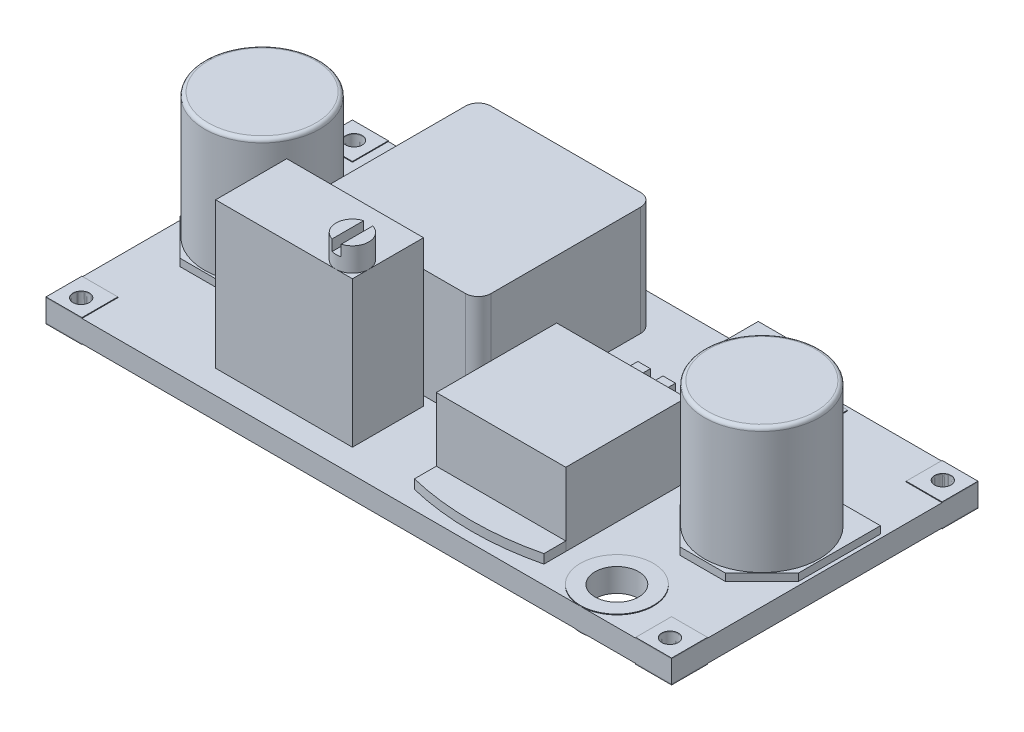
SolidWorks part; units mm, degrees
ref_plane "Front Plane" through (0, 0, 0) normal (0, 0, 1) x (1, 0, 0)
ref_plane "Top Plane" through (0, 0, 0) normal (0, 1, 0) x (1, 0, 0)
ref_plane "Right Plane" through (0, 0, 0) normal (1, 0, 0) x (0, 0, -1)
sketch "Sketch1" plane through (0, 0, 0) normal (0, 1, 0) x (1, 0, 0)
  line L1 (-21.7805, 10.668) -> (21.7805, 10.668)
  line L2 (-21.7805, 10.668) -> (-21.7805, -10.668)
  line L3 (-21.7805, -10.668) -> (21.7805, -10.668)
  line L4 (21.7805, 10.668) -> (21.7805, -10.668)
  line L5 (-21.7805, 10.668) -> (21.7805, -10.668) construction
  line L6 (-21.7805, -10.668) -> (21.7805, 10.668) construction
  circle A0 centre (-15.4305, 8.128) radius 1.651
  circle A1 centre (15.4305, -8.128) radius 1.651
  point P0 (0, 0)
  dimension "D3" = 3.302
  dimension "D1" = 43.561
  dimension "D2" = 21.336
  dimension "D4" = 6.35
  dimension "D5" = 6.35
  dimension "D6" = 2.54
  dimension "D7" = 2.54
extrude "Boss-Extrude1" add sketch "Sketch1" along normal blind 1.524
sketch "Sketch2" plane through (0, 1.524, 0) normal (0, 1, 0) x (1, 0, 0)
  line L0 (21.7805, 10.668) -> (-21.7805, 10.668) construction
  line L1 (-21.7805, -10.668) -> (21.7805, -10.668) construction
  line L3 (-21.7805, 10.668) -> (-19.2805, 10.668)
  line L4 (-21.7805, 10.668) -> (-21.7805, 8.168)
  line L5 (-21.7805, 8.168) -> (-19.2805, 8.168)
  line L6 (-19.2805, 10.668) -> (-19.2805, 8.168)
  line L7 (21.7805, 10.668) -> (19.2805, 10.668)
  line L8 (21.7805, 10.668) -> (21.7805, 8.168)
  line L9 (21.7805, 8.168) -> (19.2805, 8.168)
  line L10 (19.2805, 10.668) -> (19.2805, 8.168)
  line L11 (21.7805, -10.668) -> (19.2805, -10.668)
  line L12 (21.7805, -10.668) -> (21.7805, -8.168)
  line L13 (21.7805, -8.168) -> (19.2805, -8.168)
  line L14 (19.2805, -10.668) -> (19.2805, -8.168)
  line L15 (-21.7805, -10.668) -> (-19.2805, -10.668)
  line L16 (-21.7805, -10.668) -> (-21.7805, -8.168)
  line L17 (-21.7805, -8.168) -> (-19.2805, -8.168)
  line L18 (-19.2805, -10.668) -> (-19.2805, -8.168)
  circle A4 centre (-15.4305, 8.128) radius 1.651 construction
  circle A5 centre (15.4305, -8.128) radius 2.54
  circle A6 centre (-15.4305, 8.128) radius 2.54
  circle A9 centre (-15.4305, 8.128) radius 1.524
  circle A10 centre (-15.4305, 8.128) radius 1.524
  circle A12 centre (15.4305, -8.128) radius 1.524
  circle A13 centre (15.4305, -8.128) radius 1.524
  dimension "D3" = 2.5
  dimension "D1" = 0.127
  dimension "D2" = 0.127
extrude "Boss-Extrude2" add sketch "Sketch2" against normal offset from surface 0.0508 and the other way blind 0.0508 separate body up to face at (0, 0, 0) offset beyond the face yes
sketch "Sketch3" plane through (0, 1.524, 0) normal (0, 1, 0) x (1, 0, 0)
  line L0 (-21.5265, 4.1275) -> (-13.2715, -4.1275) construction
  line L1 (-21.5265, 4.1275) -> (-13.2715, 4.1275)
  line L2 (-21.5265, 4.1275) -> (-21.5265, -1.5875)
  line L3 (-18.9865, -4.1275) -> (-15.8115, -4.1275)
  line L4 (-13.2715, 4.1275) -> (-13.2715, -1.5875)
  line L5 (13.2715, 4.1275) -> (21.5265, 4.1275)
  line L6 (13.2715, 4.1275) -> (13.2715, -1.5875)
  line L7 (15.8115, -4.1275) -> (18.9865, -4.1275)
  line L8 (21.5265, 4.1275) -> (21.5265, -1.5875)
  line L9 (-21.7805, 10.668) -> (-21.7805, -10.668) construction
  line L10 (-21.5265, -1.5875) -> (-18.9865, -4.1275)
  line L11 (-15.8115, -4.1275) -> (-13.2715, -1.5875)
  line L12 (13.2715, -1.5875) -> (15.8115, -4.1275)
  line L13 (18.9865, -4.1275) -> (21.5265, -1.5875)
  line L14 (13.2715, -4.1275) -> (21.5265, 4.1275) construction
  line L15 (-17.399, 4.1275) -> (-17.399, -4.1275) construction
  line L16 (17.399, 4.1275) -> (17.399, -4.1275) construction
  line L17 (-17.399, 0) -> (17.399, 0) construction
  point P1 (-13.2715, -4.1275)
  point P2 (-21.5265, -4.1275)
  point P5 (21.5265, -4.1275)
  point P6 (13.2715, -4.1275)
  dimension "D1" = 8.255
  dimension "D2" = 0.254
extrude "Boss-Extrude3" add sketch "Sketch3" along normal blind 0.508 separate body
sketch "Sketch4" plane through (0, 2.032, 0) normal (0, 1, 0) x (1, 0, 0)
  circle A0 centre (-17.399, 0) radius 4.0005
  circle A1 centre (17.399, 0) radius 4.0005
  dimension "D1" = 8.001
extrude "Boss-Extrude4" add sketch "Sketch4" along normal blind 8.763 separate body
fillet "Fillet1" radius 0.254 1 edges at (-17.399, 10.795, 4.0005)
fillet "Fillet2" radius 0.254 1 edges at (17.399, 10.795, 4.0005)
sketch "Sketch5" plane through (0, 1.524, 0) normal (0, 1, 0) x (1, 0, 0)
  line L0 (21.7805, 10.668) -> (-21.7805, 10.668) construction
  line L1 (-10.2235, 8.763) -> (0.1905, 8.763)
  line L2 (-11.1125, 7.874) -> (-11.1125, -2.54)
  line L3 (-10.2235, -3.429) -> (0.1905, -3.429)
  line L4 (1.0795, 7.874) -> (1.0795, -2.54)
  line L5 (-11.1125, 8.763) -> (1.0795, -3.429) construction
  line L6 (-11.1125, -3.429) -> (1.0795, 8.763) construction
  line L7 (-21.7805, 10.668) -> (-21.7805, -10.668) construction
  arc A0 (-11.1125, -2.54) -> (-10.2235, -3.429) centre (-10.2235, -2.54) ccw
  arc A1 (0.1905, -3.429) -> (1.0795, -2.54) centre (0.1905, -2.54) ccw
  arc A2 (0.1905, 8.763) -> (1.0795, 7.874) centre (0.1905, 7.874) cw
  arc A3 (-10.2235, 8.763) -> (-11.1125, 7.874) centre (-10.2235, 7.874) ccw
  point P0 (-5.0165, 2.667)
  dimension "D4" = 0.889
  dimension "D1" = 12.192
  dimension "D2" = 1.905
  dimension "D3" = 10.668
extrude "Boss-Extrude5" add sketch "Sketch5" along normal blind 7.62 separate body
sketch "Sketch6" plane through (0, 1.524, 0) normal (0, 1, 0) x (1, 0, 0)
  line L0 (-21.7805, -10.668) -> (21.7805, -10.668) construction
  line L1 (-11.6205, -4.064) -> (-2.0955, -4.064)
  line L2 (-11.6205, -4.064) -> (-11.6205, -9.017)
  line L3 (-11.6205, -9.017) -> (-2.0955, -9.017)
  line L4 (-2.0955, -4.064) -> (-2.0955, -9.017)
  line L5 (-11.6205, -4.064) -> (-2.0955, -9.017) construction
  line L6 (-11.6205, -9.017) -> (-2.0955, -4.064) construction
  line L7 (-21.7805, 10.668) -> (-21.7805, -10.668) construction
  point P0 (-6.858, -6.5405)
  dimension "D1" = 9.525
  dimension "D2" = 4.953
  dimension "D3" = 1.651
  dimension "D4" = 10.16
extrude "Boss-Extrude6" add sketch "Sketch6" along normal blind 10.16 separate body
sketch "Sketch7" plane through (0, 11.684, 0) normal (0, 1, 0) x (1, 0, 0)
  line L0 (-11.6205, -9.017) -> (-2.0955, -9.017) construction
  line L1 (-2.0955, -9.017) -> (-2.0955, -4.064) construction
  circle A0 centre (-3.2385, -7.874) radius 1.143
  dimension "D1" = 2.286
extrude "Boss-Extrude7" add sketch "Sketch7" along normal blind 1.651
sketch "Sketch8" plane through (0, 13.335, 0) normal (0, 1, 0) x (1, 0, 0)
  line L1 (-2.921, -6.731) -> (-3.556, -6.731)
  line L2 (-2.921, -6.731) -> (-2.921, -9.017)
  line L3 (-2.921, -9.017) -> (-3.556, -9.017)
  line L4 (-3.556, -6.731) -> (-3.556, -9.017)
  line L5 (-2.921, -6.731) -> (-3.556, -9.017) construction
  line L6 (-2.921, -9.017) -> (-3.556, -6.731) construction
  circle A0 centre (-3.2385, -7.874) radius 1.143 construction
  point P0 (-3.2385, -7.874)
  dimension "D1" = 0.635
extrude "Cut-Extrude1" cut sketch "Sketch8" against normal blind 0.762
sketch "Sketch9" plane through (0, 1.524, 0) normal (0, 1, 0) x (1, 0, 0)
  line L0 (-21.7805, -10.668) -> (21.7805, -10.668) construction
  line L1 (11.6205, 0.508) -> (2.6035, 0.508)
  line L2 (11.6205, 0.508) -> (11.6205, -7.874)
  line L3 (11.6205, -7.874) -> (2.6035, -7.874)
  line L4 (2.6035, 0.508) -> (2.6035, -7.874)
  line L5 (11.6205, 0.508) -> (2.6035, -7.874) construction
  line L6 (11.6205, -7.874) -> (2.6035, 0.508) construction
  line L7 (21.7805, -10.668) -> (21.7805, 10.668) construction
  point P0 (7.112, -3.683)
  dimension "D1" = 9.017
  dimension "D2" = 8.382
  dimension "D3" = 2.794
  dimension "D4" = 10.16
extrude "Boss-Extrude8" add sketch "Sketch9" along normal blind 5.08 separate body
sketch "Sketch10" plane through (0, 1.524, 0) normal (0, 1, 0) x (1, 0, 0)
  line L0 (11.6205, -7.874) -> (11.6205, 0.508) construction
  line L1 (2.6035, -7.874) -> (11.6205, -7.874)
  line L2 (2.6035, -7.874) -> (2.6035, -9.398)
  line L4 (11.6205, -7.874) -> (11.6205, -9.398)
  arc A0 (2.6035, -9.398) -> (11.6205, -9.398) centre (7.112, 9.1108) ccw
  dimension "D2" = 19.05
  dimension "D1" = 1.524
extrude "Boss-Extrude9" add sketch "Sketch10" along normal blind 0.635 separate body
ref_plane "Plane1" through (7.112, 0, 0) normal (1, 0, 0) x (0, 0, -1)
sketch "Sketch11" plane through (7.112, 0, 0) normal (1, 0, 0) x (0, 0, -1)
  line L0 (0.508, 4.699) -> (1.4341, 4.699)
  line L1 (1.9057, 4.3797) -> (2.9203, 1.8433)
  line L2 (3.3919, 1.524) -> (5.588, 1.524)
  line L5 (-7.874, 1.524) -> (0.508, 1.524) construction
  line L6 (0.508, 6.604) -> (0.508, 1.524) construction
  line L7 (0.508, 6.604) -> (-7.874, 6.604) construction
  arc A0 (2.9203, 1.8433) -> (3.3919, 1.524) centre (3.3919, 2.032) ccw
  arc A1 (1.4341, 4.699) -> (1.9057, 4.3797) centre (1.4341, 4.191) cw
  point P15 (3.048, 1.524)
  point P18 (1.778, 4.699)
  dimension "D5" = 0.508
  dimension "D1" = 1.27
  dimension "D2" = 1.905
  dimension "D3" = 2.54
  dimension "D4" = 2.54
extrude "Extrude-Thin1" add sketch "Sketch11" along normal mid plane 7.874 separate body thin
sketch "Sketch12" plane through (0, 5.207, 0) normal (0, 1, 0) x (1, 0, 0)
  line L0 (11.049, 5.588) -> (3.175, 5.588) construction
  line L1 (4.0499, 5.588) -> (4.9248, 5.588)
  line L2 (4.0499, 5.588) -> (4.0499, 0.508)
  line L3 (4.0499, 0.508) -> (4.9248, 0.508)
  line L4 (4.9248, 5.588) -> (4.9248, 0.508)
  line L5 (11.049, 0.508) -> (3.175, 0.508) construction
  line L6 (5.7997, 5.588) -> (5.7997, 0.508)
  line L7 (5.7997, 5.588) -> (6.6746, 5.588)
  line L8 (6.6746, 5.588) -> (6.6746, 0.508)
  line L9 (5.7997, 0.508) -> (6.6746, 0.508)
  line L10 (7.5494, 5.588) -> (7.5494, 0.508)
  line L11 (7.5494, 5.588) -> (8.4243, 5.588)
  line L12 (8.4243, 5.588) -> (8.4243, 0.508)
  line L13 (7.5494, 0.508) -> (8.4243, 0.508)
  line L14 (9.2992, 5.588) -> (9.2992, 0.508)
  line L15 (9.2992, 5.588) -> (10.1741, 5.588)
  line L16 (10.1741, 5.588) -> (10.1741, 0.508)
  line L17 (9.2992, 0.508) -> (10.1741, 0.508)
  line L18 (3.175, 3.3919) -> (4.0499, 3.3919) construction
  line L19 (11.049, 3.3919) -> (3.175, 3.3919) construction
  line L20 (4.9248, 3.3919) -> (5.7997, 3.3919) construction
  line L21 (6.6746, 3.3919) -> (7.5494, 3.3919) construction
  line L22 (8.4243, 3.3919) -> (9.2992, 3.3919) construction
  line L23 (10.1741, 3.3919) -> (11.049, 3.3919) construction
  dimension "D1" = 4
extrude "Cut-Extrude2" cut sketch "Sketch12" against normal up to next
sketch "Sketch13" plane through (0, 1.524, 0) normal (0, 1, 0) x (1, 0, 0)
  line L0 (21.7805, 10.668) -> (-21.7805, 10.668) construction
  line L1 (6.985, 10.16) -> (11.049, 10.16)
  line L2 (6.985, 10.16) -> (6.985, 7.62)
  line L3 (6.985, 7.62) -> (11.049, 7.62)
  line L4 (11.049, 10.16) -> (11.049, 7.62)
  line L5 (11.049, 3.3919) -> (11.049, 5.588) construction
  dimension "D1" = 4.064
  dimension "D2" = 2.54
  dimension "D3" = 0.508
extrude "Boss-Extrude10" add sketch "Sketch13" along normal blind 2.54 separate body
sketch "Sketch14" plane through (0, 1.524, 0) normal (0, 1, 0) x (1, 0, 0)
  line L0 (7.62, 8.89) -> (10.414, 8.89) construction
  line L1 (5.08, 10.414) -> (7.62, 10.414)
  line L2 (5.08, 10.414) -> (5.08, 7.366)
  line L3 (5.08, 7.366) -> (7.62, 7.366)
  line L4 (7.62, 10.414) -> (7.62, 7.366)
  line L5 (12.954, 7.366) -> (10.414, 7.366)
  line L6 (12.954, 7.366) -> (12.954, 10.414)
  line L7 (12.954, 10.414) -> (10.414, 10.414)
  line L8 (10.414, 7.366) -> (10.414, 10.414)
  line L9 (9.017, 7.62) -> (9.017, 10.16) construction
  line L10 (6.985, 7.62) -> (11.049, 7.62) construction
  line L11 (11.049, 10.16) -> (6.985, 10.16) construction
  dimension "D1" = 2.54
  dimension "D2" = 3.048
  dimension "D3" = 2.794
extrude "Boss-Extrude11" add sketch "Sketch14" along normal blind 0.0508 separate body
sketch "Sketch15" plane through (0, 0, 0) normal (0, -1, 0) x (1, 0, 0)
  line L0 (7.5, 0) -> (-7.5, 0) construction
  line L1 (-7.5, 0) -> (-3.9645, 3.5355) construction
  line L2 (-7.5, 0) -> (-3.9645, -3.5355) construction
  line L3 (-3.9645, 3.5355) -> (-3.9645, -3.5355) construction
  line L5 (-8.2071, -0.7071) -> (-4.6716, -4.2426)
  line L6 (7.5, 1) -> (-5.0858, 1)
  line L7 (-8.2071, 0.7071) -> (-4.6716, 4.2426)
  line L8 (-5.0858, -1) -> (-3.2574, -2.8284)
  line L9 (7.5, -1) -> (-5.0858, -1)
  line L10 (-5.0858, 1) -> (-3.2574, 2.8284)
  line L12 (-6.7929, 0.7071) -> (-3.2574, -2.8284) construction
  line L13 (7.5, 1) -> (-7.5, 1) construction
  line L14 (7.5, -1) -> (-7.5, -1) construction
  arc A0 (-8.2071, -0.7071) -> (-8.2071, 0.7071) centre (-7.5, 0) cw
  arc A1 (-3.2574, 2.8284) -> (-4.6716, 4.2426) centre (-3.9645, 3.5355) ccw
  arc A2 (-8.2071, -0.7071) -> (-8.2071, 0.7071) centre (-7.5, 0) cw
  arc A3 (-4.6716, -4.2426) -> (-3.2574, -2.8284) centre (-3.9645, -3.5355) ccw
  arc A4 (7.5, 1) -> (7.5, -1) centre (7.5, 0) cw
  arc A5 (-8.2071, 0.7071) -> (-8.2071, -0.7071) centre (-7.5, 0) ccw
  point P5 (-3.9645, 0)
  dimension "D1" = 15
  dimension "D2" = 5
  dimension "D3" = 1
  dimension "D4" = 1
extrude "Boss-Extrude12" add sketch "Sketch15" along normal blind 0.01 contours A4 L6 L10 A1 L7 A0 L5 A3 L8 L9
hole_wizard "Ø1.15 (1.15) Diameter Hole1" positions "Sketch16" profile "Sketch17" hole size "Ø1.15" standard "ANSI Metric" end condition through all
sketch "Sketch16" plane through (0, 1.5748, 0) normal (0, 1, 0) x (1, 0, 0)
  line L1 (-20.5, 9.5) -> (20.5, 9.5)
  line L2 (-20.5, 9.5) -> (-20.5, -9.5)
  line L3 (-20.5, -9.5) -> (20.5, -9.5)
  line L4 (20.5, 9.5) -> (20.5, -9.5)
  line L5 (-20.5, 0) -> (20.5, 0) construction
  point P0 (-20.5, -9.5)
  point P2 (-20.5, 9.5)
  point P4 (20.5, 9.5)
  point P6 (20.5, -9.5)
  dimension "D1" = 41
  dimension "D2" = 19
sketch "Sketch17" plane through (-20.5, 1.5748, 9.5) normal (1, 0, 0) x (0, 0, 1)
  line L0 (0, 0) -> (0, 1.6256)
  line L1 (0, 1.6256) -> (0.575, 1.6256)
  line L2 (0.575, 1.6256) -> (0.575, 0)
  line L5 (0.575, 0) -> (0, 0)
  line L11 (0, -6.35) -> (0, 107.95) construction
  dimension "Thru Hole Dia." = 1.15
  dimension "Thru Hole Depth" = 1.6256
